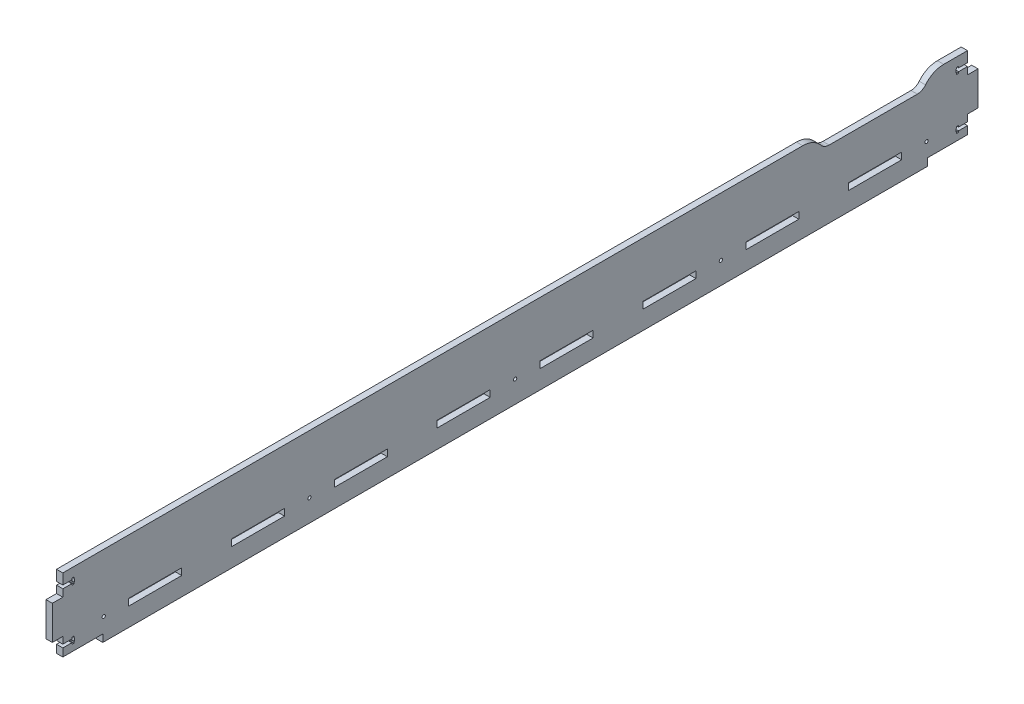
SolidWorks part; units mm, degrees
ref_plane "Płaszczyzna przednia" through (0, 0, 0) normal (0, 0, 1) x (1, 0, 0)
ref_plane "Płaszczyzna górna" through (0, 0, 0) normal (0, 1, 0) x (1, 0, 0)
ref_plane "Płaszczyzna prawa" through (0, 0, 0) normal (1, 0, 0) x (0, 0, -1)
sketch "Szkic1" plane through (0, 0, 0) normal (0, 0, 1) x (1, 0, 0)
  line L0 (584.8019, -458.604) -> (594.8019, -458.604)
  line L1 (584.8019, -458.604) -> (584.8019, -386.324)
  line L2 (594.8019, -458.604) -> (594.8019, -386.324)
  line L3 (584.8019, -386.324) -> (594.8019, -386.324)
  line L4 (572.8019, -508.604) -> (610.8019, -508.604) construction
  dimension "D1" = 72.28
  dimension "D2" = 10
  dimension "D3" = 50
extrude "Dodanie-wyciągnięcie1" add sketch "Szkic1" against normal blind 880
sketch "Szkic3" plane through (594.8019, 0, 0) normal (1, 0, 0) x (0, 0, -1)
  line L0 (713.4049, -386.324) -> (847.407, -386.324)
  line L1 (880, -386.324) -> (0, -386.324) construction
  line L2 (880, -458.604) -> (880, -386.324) construction
  line L3 (822.3149, -398.324) -> (738.497, -398.324)
  arc A0 (830.0993, -394.6012) -> (847.407, -386.324) centre (847.407, -408.5578) cw
  arc A1 (830.0993, -394.6012) -> (822.3149, -398.324) centre (822.3149, -388.324) cw
  arc A2 (730.7126, -394.6012) -> (738.497, -398.324) centre (738.497, -388.324) ccw
  arc A3 (730.7126, -394.6012) -> (713.4049, -386.324) centre (713.4049, -408.5578) ccw
  dimension "D1" = 12
  dimension "D2" = 10
  dimension "D3" = 22.2338
  dimension "D4" = 10
  dimension "D5" = 22.2338
  dimension "D6" = 7.7844
  dimension "D7" = 7.7844
  dimension "D8" = 32.593
  dimension "D9" = 108.91
extrude "Wytnij-wyciągnięcie1" cut sketch "Szkic3" against normal blind 10
other "Przenieś ścianę1" face at (594.8019, -404.6194, -644.2436) parameters "D1"=4
sketch "Szkic10" plane through (590.8019, 0, 0) normal (1, 0, 0) x (0, 0, -1)
  line L0 (50.44, -444.7627) -> (50.44, -438.7627) construction
  line L1 (47.34, -444.7627) -> (47.34, -438.7627) construction
  line L18 (50.44, -444.7627) -> (50.44, -438.7627)
  line L19 (47.34, -444.7627) -> (47.34, -438.7627)
  line L36 (50.44, -441.7627) -> (47.34, -441.7627)
  circle A0 centre (48.89, -441.7627) radius 1.55
  dimension "D1" = 3.1
sketch "Szkic11" plane through (584.8019, 0, 0) normal (-1, 0, 0) x (0, 0, 1)
  circle A0 centre (-48.89, -441.7627) radius 1.55 construction
  circle A1 centre (-48.89, -441.7627) radius 1.55
extrude "Wytnij-wyciągnięcie5" cut sketch "Szkic11" against normal blind 6
pattern_linear "Szyk liniowy2" count 5 spacing 195.556 along (0, 0, -1) of "Wytnij-wyciągnięcie5"
ref_plane "Płaszczyzna1" through (0, 0, -440) normal (0, 0, 1) x (1, 0, 0)
sketch "Szkic4" plane through (584.8019, 0, 0) normal (-1, 0, 0) x (0, 0, 1)
  line L0 (0, -386.324) -> (-10, -386.324)
  line L1 (0, -386.324) -> (0, -406.324)
  line L2 (-10, -386.324) -> (-10, -406.324)
  line L3 (0, -406.324) -> (-10, -406.324)
  line L4 (-713.4049, -386.324) -> (0, -386.324) construction
  line L5 (0, -458.604) -> (-10, -458.604)
  line L6 (0, -458.604) -> (0, -438.604)
  line L7 (-10, -458.604) -> (-10, -438.604)
  line L8 (0, -438.604) -> (-10, -438.604)
  line L9 (0, -386.324) -> (0, -458.604) construction
  line L10 (-880, -458.604) -> (0, -458.604) construction
  dimension "D1" = 10
  dimension "D2" = 10
  dimension "D3" = 20
  dimension "D4" = 20
  dimension "D5" = 0
extrude "Wytnij-wyciągnięcie2" cut sketch "Szkic4" against normal blind 10
mirror "Lustro2" about plane through (0, 0, -440) normal (0, 0, 1) of "Wytnij-wyciągnięcie2"
sketch "Szkic12" plane through (584.8019, 0, 0) normal (-1, 0, 0) x (0, 0, 1)
  line L0 (-832, -458.604) -> (-48, -458.604)
  line L1 (-832, -458.604) -> (-832, -464.604)
  line L2 (-48, -458.604) -> (-48, -464.604)
  line L3 (-832, -464.604) -> (-48, -464.604)
  line L4 (-870, -458.604) -> (-10, -458.604) construction
  line L6 (-10, -438.604) -> (-10, -458.604) construction
  line L8 (-870, -438.604) -> (-870, -458.604) construction
  dimension "D1" = 6
  dimension "D2" = 38
  dimension "D3" = 38
extrude "Dodanie-wyciągnięcie2" add sketch "Szkic12" against normal blind 6
sketch "Szkic15" plane through (584.8019, 0, 0) normal (-1, 0, 0) x (0, 0, 1)
  line L0 (-832, -458.604) -> (-870, -458.604)
  line L1 (-832, -458.604) -> (-832, -455.604)
  line L2 (-870, -458.604) -> (-870, -455.604)
  line L3 (-832, -455.604) -> (-870, -455.604)
  line L4 (-48, -458.604) -> (-10, -458.604)
  line L5 (-48, -458.604) -> (-48, -455.604)
  line L6 (-10, -458.604) -> (-10, -455.604)
  line L7 (-48, -455.604) -> (-10, -455.604)
  dimension "D1" = 3
  dimension "D2" = 3
extrude "Wytnij-wyciągnięcie8" cut sketch "Szkic15" against normal blind 6
sketch "Szkic13" plane through (584.8019, 0, 0) normal (-1, 0, 0) x (0, 0, 1)
  line L0 (-832, -464.604) -> (-832, -462.604)
  line L1 (-832, -464.604) -> (-48, -464.604)
  line L2 (-832, -462.604) -> (-48, -462.604)
  line L3 (-48, -464.604) -> (-48, -462.604)
  line L4 (-832, -455.604) -> (-832, -464.604) construction
  line L6 (-48, -464.604) -> (-48, -455.604) construction
  dimension "D1" = 2
  dimension "D2" = 0
extrude "Wytnij-wyciągnięcie6" cut sketch "Szkic13" against normal through all
sketch "Szkic5" plane through (584.8019, 0, 0) normal (-1, 0, 0) x (0, 0, 1)
  line L0 (-21, -396.324) -> (-20.5, -396.324)
  line L1 (-21, -396.324) -> (-21, -399.424)
  line L2 (-10, -396.324) -> (-10, -399.424)
  line L3 (-21, -399.424) -> (-20.5, -399.424)
  line L5 (-20.5, -394.949) -> (-20.5, -396.324)
  line L6 (-20.5, -394.949) -> (-18.5, -394.949)
  line L7 (-20.5, -400.799) -> (-18.5, -400.799)
  line L8 (-18.5, -394.949) -> (-18.5, -396.324)
  line L9 (-18.5, -396.324) -> (-10, -396.324)
  line L10 (-20.5, -399.424) -> (-20.5, -400.799)
  line L11 (-18.5, -399.424) -> (-10, -399.424)
  line L12 (-18.5, -399.424) -> (-18.5, -400.799)
  line L15 (-10, -386.324) -> (-10, -406.324) construction
  point P0 (-10, -396.324)
  dimension "D1" = 11
  dimension "D2" = 3.1
  dimension "D3" = 5.85
  dimension "D4" = 2
  dimension "D5" = 1.375
  dimension "D6" = 0.5
  dimension "D7" = 0
extrude "Wytnij-wyciągnięcie3" cut sketch "Szkic5" against normal blind 10
pattern_linear "Szyk liniowy1" count 2 spacing 48.68 along (0, -1, 0) of "Wytnij-wyciągnięcie3"
mirror "Lustro1" about plane through (0, 0, -440) normal (0, 0, 1) of "Wytnij-wyciągnięcie3", "Szyk liniowy1"
sketch "Szkic7" plane through (584.8019, 0, 0) normal (-1, 0, 0) x (0, 0, 1)
  line L48 (-122.776, -444.7627) -> (-72.776, -444.7627)
  line L49 (-72.776, -444.7627) -> (-72.776, -438.7627)
  line L50 (-72.776, -438.7627) -> (-122.776, -438.7627)
  line L51 (-122.776, -438.7627) -> (-122.776, -444.7627)
  line L52 (-220.554, -444.7627) -> (-170.554, -444.7627)
  line L53 (-170.554, -444.7627) -> (-170.554, -438.7627)
  line L54 (-170.554, -438.7627) -> (-220.554, -438.7627)
  line L55 (-220.554, -438.7627) -> (-220.554, -444.7627)
  line L56 (-318.332, -444.7627) -> (-268.332, -444.7627)
  line L57 (-268.332, -444.7627) -> (-268.332, -438.7627)
  line L58 (-268.332, -438.7627) -> (-318.332, -438.7627)
  line L59 (-318.332, -438.7627) -> (-318.332, -444.7627)
  line L60 (-416.11, -444.7627) -> (-366.11, -444.7627)
  line L61 (-366.11, -444.7627) -> (-366.11, -438.7627)
  line L62 (-366.11, -438.7627) -> (-416.11, -438.7627)
  line L63 (-416.11, -438.7627) -> (-416.11, -444.7627)
  line L64 (-513.888, -444.7627) -> (-463.888, -444.7627)
  line L65 (-463.888, -444.7627) -> (-463.888, -438.7627)
  line L66 (-463.888, -438.7627) -> (-513.888, -438.7627)
  line L67 (-513.888, -438.7627) -> (-513.888, -444.7627)
  line L68 (-611.666, -444.7627) -> (-561.666, -444.7627)
  line L69 (-561.666, -444.7627) -> (-561.666, -438.7627)
  line L70 (-561.666, -438.7627) -> (-611.666, -438.7627)
  line L71 (-611.666, -438.7627) -> (-611.666, -444.7627)
  line L72 (-709.444, -444.7627) -> (-659.444, -444.7627)
  line L73 (-659.444, -444.7627) -> (-659.444, -438.7627)
  line L74 (-659.444, -438.7627) -> (-709.444, -438.7627)
  line L75 (-709.444, -438.7627) -> (-709.444, -444.7627)
  line L76 (-807.222, -444.7627) -> (-757.222, -444.7627)
  line L77 (-757.222, -444.7627) -> (-757.222, -438.7627)
  line L78 (-757.222, -438.7627) -> (-807.222, -438.7627)
  line L79 (-807.222, -438.7627) -> (-807.222, -444.7627)
  line L80 (-757.022, -438.5627) -> (-807.422, -438.5627)
  line L81 (-807.422, -438.5627) -> (-807.422, -444.9627)
  line L82 (-807.422, -444.9627) -> (-757.022, -444.9627)
  line L83 (-757.022, -444.9627) -> (-757.022, -438.5627)
  line L84 (-659.244, -438.5627) -> (-709.644, -438.5627)
  line L85 (-709.644, -438.5627) -> (-709.644, -444.9627)
  line L86 (-709.644, -444.9627) -> (-659.244, -444.9627)
  line L87 (-659.244, -444.9627) -> (-659.244, -438.5627)
  line L88 (-611.866, -444.9627) -> (-561.466, -444.9627)
  line L89 (-561.466, -444.9627) -> (-561.466, -438.5627)
  line L90 (-561.466, -438.5627) -> (-611.866, -438.5627)
  line L91 (-611.866, -438.5627) -> (-611.866, -444.9627)
  line L92 (-514.088, -444.9627) -> (-463.688, -444.9627)
  line L93 (-463.688, -444.9627) -> (-463.688, -438.5627)
  line L94 (-463.688, -438.5627) -> (-514.088, -438.5627)
  line L95 (-514.088, -438.5627) -> (-514.088, -444.9627)
  line L96 (-416.31, -444.9627) -> (-365.91, -444.9627)
  line L97 (-365.91, -444.9627) -> (-365.91, -438.5627)
  line L98 (-365.91, -438.5627) -> (-416.31, -438.5627)
  line L99 (-416.31, -438.5627) -> (-416.31, -444.9627)
  line L100 (-318.532, -444.9627) -> (-268.132, -444.9627)
  line L101 (-268.132, -444.9627) -> (-268.132, -438.5627)
  line L102 (-268.132, -438.5627) -> (-318.532, -438.5627)
  line L103 (-318.532, -438.5627) -> (-318.532, -444.9627)
  line L104 (-220.754, -444.9627) -> (-170.354, -444.9627)
  line L105 (-170.354, -444.9627) -> (-170.354, -438.5627)
  line L106 (-170.354, -438.5627) -> (-220.754, -438.5627)
  line L107 (-220.754, -438.5627) -> (-220.754, -444.9627)
  line L108 (-122.976, -444.9627) -> (-106.5066, -444.9627)
  line L109 (-72.576, -444.9627) -> (-72.576, -438.5627)
  line L110 (-106.4683, -438.5627) -> (-122.976, -438.5627)
  line L111 (-122.976, -438.5627) -> (-122.976, -444.9627)
  line L116 (-106.5066, -444.9627) -> (-72.576, -444.9627)
  line L118 (-72.576, -438.5627) -> (-106.4683, -438.5627)
  point P0 (-78, -444.7627)
  point P1 (-45, -444.7627)
  point P3 (-45, -438.7627)
  point P4 (-78, -438.7627)
  point P77 (-44.8, -444.9627)
  point P78 (-44.8, -438.5627)
sketch "Szkic8" plane through (584.8019, 0, 0) normal (-1, 0, 0) x (0, 0, 1)
  line L12 (-170.354, -438.5627) -> (-220.754, -438.5627) construction
  line L13 (-220.754, -438.5627) -> (-220.754, -444.9627) construction
  line L14 (-220.754, -444.9627) -> (-170.354, -444.9627) construction
  line L15 (-170.354, -444.9627) -> (-170.354, -438.5627) construction
  line L16 (-268.132, -438.5627) -> (-318.532, -438.5627) construction
  line L17 (-318.532, -438.5627) -> (-318.532, -444.9627) construction
  line L18 (-318.532, -444.9627) -> (-268.132, -444.9627) construction
  line L19 (-268.132, -444.9627) -> (-268.132, -438.5627) construction
  line L20 (-365.91, -438.5627) -> (-416.31, -438.5627) construction
  line L21 (-416.31, -438.5627) -> (-416.31, -444.9627) construction
  line L22 (-416.31, -444.9627) -> (-365.91, -444.9627) construction
  line L23 (-365.91, -444.9627) -> (-365.91, -438.5627) construction
  line L24 (-463.688, -438.5627) -> (-514.088, -438.5627) construction
  line L25 (-514.088, -438.5627) -> (-514.088, -444.9627) construction
  line L26 (-514.088, -444.9627) -> (-463.688, -444.9627) construction
  line L27 (-463.688, -444.9627) -> (-463.688, -438.5627) construction
  line L28 (-561.466, -438.5627) -> (-611.866, -438.5627) construction
  line L29 (-611.866, -438.5627) -> (-611.866, -444.9627) construction
  line L30 (-611.866, -444.9627) -> (-561.466, -444.9627) construction
  line L31 (-561.466, -444.9627) -> (-561.466, -438.5627) construction
  line L32 (-709.644, -438.5627) -> (-709.644, -444.9627) construction
  line L33 (-709.644, -444.9627) -> (-659.244, -444.9627) construction
  line L34 (-659.244, -444.9627) -> (-659.244, -438.5627) construction
  line L35 (-659.244, -438.5627) -> (-709.644, -438.5627) construction
  line L36 (-757.022, -438.5627) -> (-807.422, -438.5627) construction
  line L37 (-807.422, -438.5627) -> (-807.422, -444.9627) construction
  line L38 (-807.422, -444.9627) -> (-757.022, -444.9627) construction
  line L39 (-757.022, -444.9627) -> (-757.022, -438.5627) construction
  line L40 (-106.4683, -438.5627) -> (-122.976, -438.5627) construction
  line L41 (-122.976, -438.5627) -> (-122.976, -444.9627) construction
  line L42 (-122.976, -444.9627) -> (-106.5066, -444.9627) construction
  line L43 (-106.5066, -444.9627) -> (-72.576, -444.9627) construction
  line L44 (-72.576, -444.9627) -> (-72.576, -438.5627) construction
  line L45 (-72.576, -438.5627) -> (-106.4683, -438.5627) construction
  line L46 (-106.4683, -438.5627) -> (-122.976, -438.5627)
  line L47 (-122.976, -438.5627) -> (-122.976, -444.9627)
  line L48 (-122.976, -444.9627) -> (-106.5066, -444.9627)
  line L49 (-106.5066, -444.9627) -> (-72.576, -444.9627)
  line L50 (-72.576, -444.9627) -> (-72.576, -438.5627)
  line L51 (-72.576, -438.5627) -> (-106.4683, -438.5627)
  line L52 (-170.354, -438.5627) -> (-220.754, -438.5627)
  line L53 (-220.754, -438.5627) -> (-220.754, -444.9627)
  line L54 (-220.754, -444.9627) -> (-170.354, -444.9627)
  line L55 (-170.354, -444.9627) -> (-170.354, -438.5627)
  line L56 (-268.132, -438.5627) -> (-318.532, -438.5627)
  line L57 (-318.532, -438.5627) -> (-318.532, -444.9627)
  line L58 (-318.532, -444.9627) -> (-268.132, -444.9627)
  line L59 (-268.132, -444.9627) -> (-268.132, -438.5627)
  line L60 (-365.91, -438.5627) -> (-416.31, -438.5627)
  line L61 (-416.31, -438.5627) -> (-416.31, -444.9627)
  line L62 (-416.31, -444.9627) -> (-365.91, -444.9627)
  line L63 (-365.91, -444.9627) -> (-365.91, -438.5627)
  line L64 (-463.688, -438.5627) -> (-514.088, -438.5627)
  line L65 (-514.088, -438.5627) -> (-514.088, -444.9627)
  line L66 (-514.088, -444.9627) -> (-463.688, -444.9627)
  line L67 (-463.688, -444.9627) -> (-463.688, -438.5627)
  line L68 (-561.466, -438.5627) -> (-611.866, -438.5627)
  line L69 (-611.866, -438.5627) -> (-611.866, -444.9627)
  line L70 (-611.866, -444.9627) -> (-561.466, -444.9627)
  line L71 (-561.466, -444.9627) -> (-561.466, -438.5627)
  line L72 (-709.644, -438.5627) -> (-709.644, -444.9627)
  line L73 (-709.644, -444.9627) -> (-659.244, -444.9627)
  line L74 (-659.244, -444.9627) -> (-659.244, -438.5627)
  line L75 (-659.244, -438.5627) -> (-709.644, -438.5627)
  line L76 (-757.022, -438.5627) -> (-807.422, -438.5627)
  line L77 (-807.422, -438.5627) -> (-807.422, -444.9627)
  line L78 (-807.422, -444.9627) -> (-757.022, -444.9627)
  line L79 (-757.022, -444.9627) -> (-757.022, -438.5627)
extrude "Wytnij-wyciągnięcie4" cut sketch "Szkic8" against normal blind 6
equation "\"tolerancja_wpustu_10_gl\"=10.1"
equation "\"tolerancja_wpusy\"=0.2"
equation "\"dlugosc_wpustu_duzy\"=20"
equation "\"srednica_otworu_M3\"=3.1"
equation "\"szerokosc_nogi_T\"=3.1"
equation "\"dlugosc_T_30\"=11"
equation "\"grubosc_na_nakretke_kwadrat\"=2"
equation "\"szerokosc_na_nakretke_kwadrat\"=5.85"
equation "\"wyokosc_nadstawki_T\"=0.5"
equation "\"D2@Szkic5\"=\"szerokosc_nogi_T\""
equation "\"D3@Szkic5\"=\"szerokosc_na_nakretke_kwadrat\""
equation "\"D4@Szkic5\"=\"grubosc_na_nakretke_kwadrat\""
equation "\"D5@Szkic5\"=(\"szerokosc_na_nakretke_kwadrat\"-\"szerokosc_nogi_T\")/2"
equation "\"D6@Szkic5\"=\"wyokosc_nadstawki_T\""
equation "\"D1@Szkic10\"=\"srednica_otworu_M3\""
